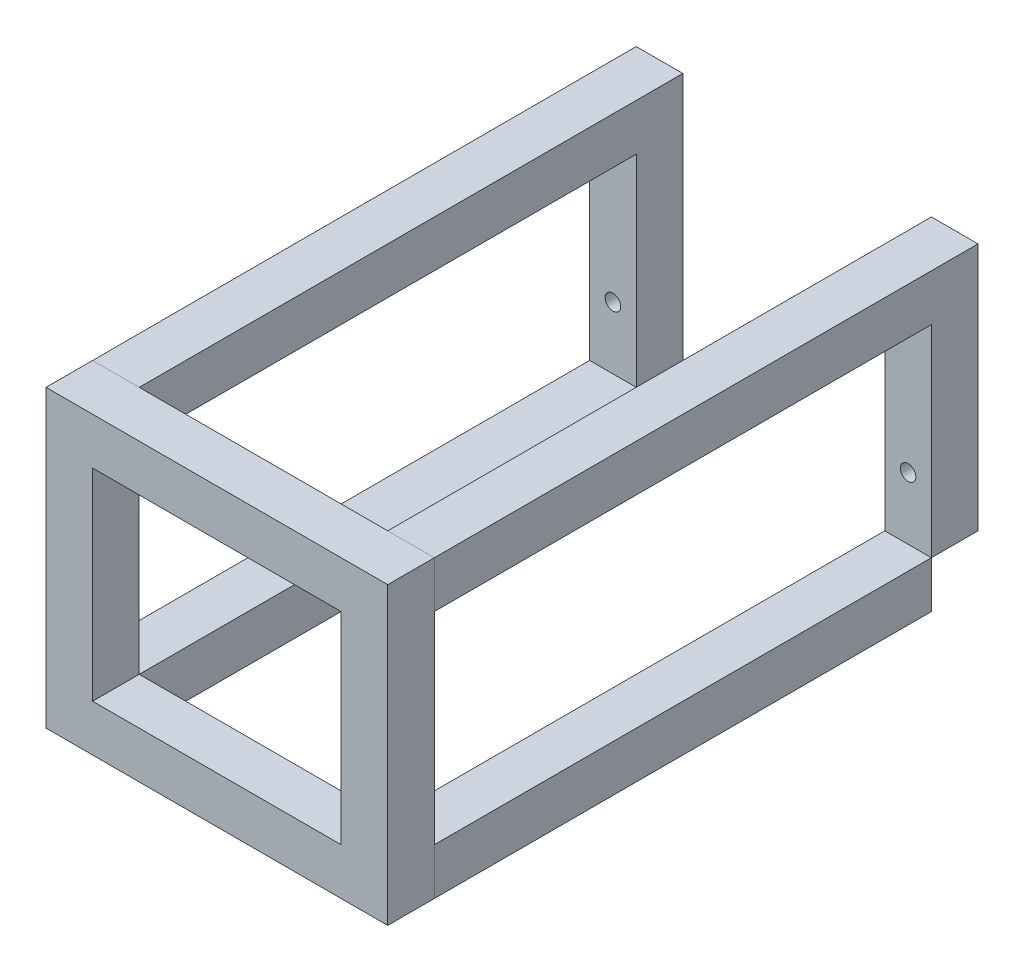
SolidWorks part; units mm, degrees
ref_plane "Front Plane" through (0, 0, 0) normal (0, 0, 1) x (1, 0, 0)
ref_plane "Top Plane" through (0, 0, 0) normal (0, 1, 0) x (1, 0, 0)
ref_plane "Right Plane" through (0, 0, 0) normal (1, 0, 0) x (0, 0, -1)
sketch "Sketch1" plane through (0, 0, 0) normal (0, 0, 1) x (1, 0, 0)
  line B0 (260.6939, -24.8034) -> (-51.6659, -24.8034)
  line B1 (-146.311, -32.7409) -> (-70.111, -32.7409)
  line B2 (-146.311, 37.1091) -> (-146.311, -32.7409)
  line B3 (336.289, 56.1591) -> (-127.261, 56.1591)
  circle B4 centre (-38.361, 40.2841) radius 4.7625
  circle B5 centre (-38.361, 40.2841) radius 6.35
  circle B6 centre (56.889, 40.2841) radius 4.7625
  circle B7 centre (56.889, 40.2841) radius 6.35
  arc B8 (-51.6659, -24.8034) -> (-70.111, -32.7409) centre (-51.6659, -50.2034) ccw
  arc B9 (-127.261, 56.1591) -> (-146.311, 37.1091) centre (-127.261, 37.1091) ccw
sketch_block_instance "Block1-1"
sketch_block "Block1"
sketch "Sketch2" plane through (0, 0, 0) normal (0, 0, 1) x (1, 0, 0)
  line L0 (-38.361, 56.1591) -> (-38.361, -24.8034) construction
  line L1 (-95.511, 68.8591) -> (-76.461, 68.8591)
  line L2 (-95.511, 68.8591) -> (-95.511, -32.7409)
  line L3 (-95.511, -32.7409) -> (-76.461, -32.7409)
  line L4 (-76.461, 68.8591) -> (-76.461, -32.7409)
  line L5 (25.139, 68.8591) -> (44.189, 68.8591)
  line L6 (25.139, 68.8591) -> (25.139, -32.7409)
  line L7 (25.139, -32.7409) -> (44.189, -32.7409)
  line L8 (44.189, 68.8591) -> (44.189, -32.7409)
  line L9 (336.289, 56.1591) -> (-127.261, 56.1591) construction
  line L10 (260.6939, -24.8034) -> (-51.6659, -24.8034) construction
  line L11 (-146.311, -32.7409) -> (-70.111, -32.7409) construction
  circle A0 centre (-85.986, -7.3409) radius 3.175
  circle A1 centre (34.664, -7.3409) radius 3.175
  point P4 (0, 0)
  point P16 (-85.986, 68.8591)
  point P21 (0, 0)
  point P22 (34.664, 68.8591)
  point P23 (0, 0)
  point P25 (0, 0)
  point P28 (-85.986, -32.7409)
  point P29 (-85.986, -32.7409)
  point P30 (0, 0)
  dimension "D7" = 6.35
  dimension "D8" = 6.35
  dimension "D9" = 76.2
  dimension "D1" = 19.05
  dimension "D2" = 19.05
  dimension "D3" = 101.6
  dimension "D4" = 101.6
  dimension "D5" = 63.5
  dimension "D6" = 38.1
extrude "Boss-Extrude1" add sketch "Sketch2" along normal blind 19.05
sketch "Sketch3" plane through (0, 0, 19.05) normal (0, 0, 1) x (1, 0, 0)
  line L0 (-76.461, -32.7409) -> (-76.461, 68.8591) construction
  line L1 (-95.511, 68.8591) -> (-76.461, 68.8591)
  line L2 (-95.511, 68.8591) -> (-95.511, 49.8091)
  line L3 (-95.511, 49.8091) -> (-76.461, 49.8091)
  line L4 (-76.461, 68.8591) -> (-76.461, 49.8091)
  line L5 (44.189, -32.7409) -> (44.189, 68.8591) construction
  line L6 (25.139, 68.8591) -> (44.189, 68.8591)
  line L7 (25.139, 68.8591) -> (25.139, 49.8091)
  line L8 (25.139, 49.8091) -> (44.189, 49.8091)
  line L9 (44.189, 68.8591) -> (44.189, 49.8091)
  line L11 (-95.511, -32.7409) -> (-76.461, -32.7409)
  line L12 (-95.511, -32.7409) -> (-95.511, -51.7909)
  line L13 (-95.511, -51.7909) -> (-76.461, -51.7909)
  line L14 (-76.461, -32.7409) -> (-76.461, -51.7909)
  line L15 (25.139, -32.7409) -> (44.189, -32.7409)
  line L16 (25.139, -32.7409) -> (25.139, -51.7909)
  line L17 (25.139, -51.7909) -> (44.189, -51.7909)
  line L18 (44.189, -32.7409) -> (44.189, -51.7909)
  dimension "D1" = 19.05
  dimension "D2" = 19.05
  dimension "D3" = 19.05
  dimension "D4" = 19.05
  dimension "D5" = 19.05
  dimension "D6" = 19.05
extrude "Boss-Extrude2" add sketch "Sketch3" along normal blind 203.2
sketch "Sketch4" plane through (0, 0, 222.25) normal (0, 0, 1) x (1, 0, 0)
  line L0 (-95.511, 68.8591) -> (-95.511, -51.7909)
  line L1 (-95.511, -51.7909) -> (44.189, -51.7909)
  line L2 (44.189, -51.7909) -> (44.189, 68.8591)
  line L3 (44.189, 68.8591) -> (-95.511, 68.8591)
  line L5 (-76.461, 49.8091) -> (25.139, 49.8091)
  line L6 (-76.461, 49.8091) -> (-76.461, -32.7409)
  line L7 (-76.461, -32.7409) -> (25.139, -32.7409)
  line L8 (25.139, 49.8091) -> (25.139, -32.7409)
extrude "Boss-Extrude6" add sketch "Sketch4" along normal blind 19.05 separate body
